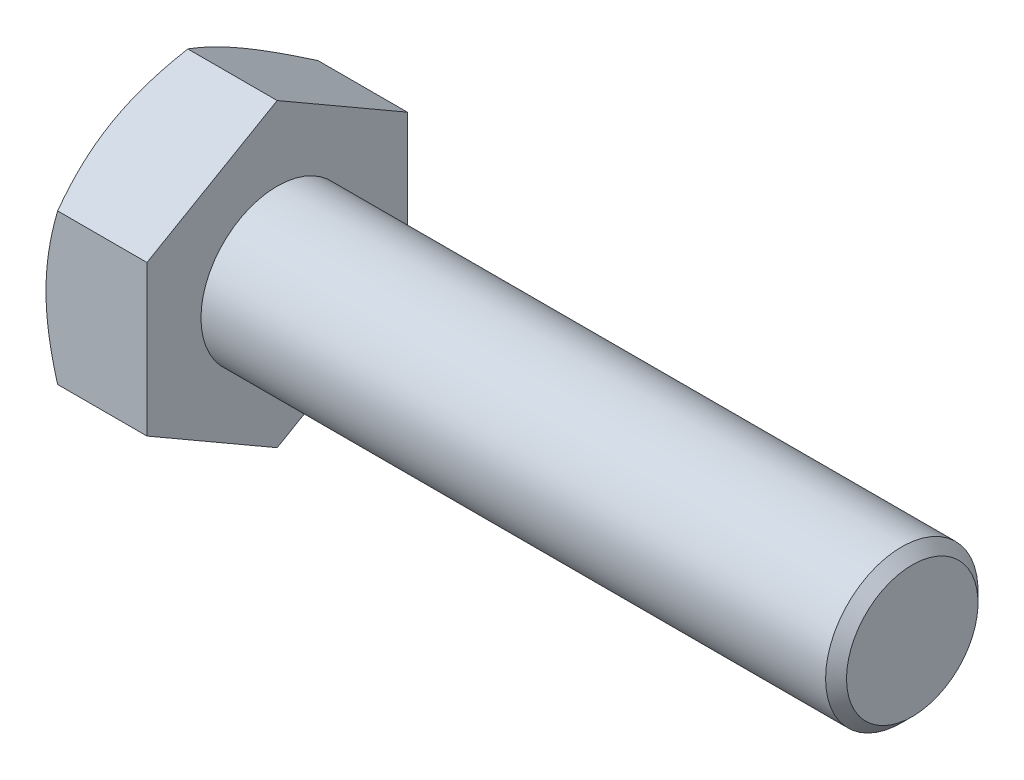
SolidWorks part; units mm, degrees
extrude "BaseHead" add sketch "Sketch1" along normal blind 15.9
sketch "Sketch1" plane through (0, 0, 0) normal (1, 0, 0) x (0, 0, -1)
  line L0 (20.5, 11.8357) -> (20.5, -11.8357)
  line L1 (-20.5, 11.8357) -> (-20.5, -11.8357)
  line L2 (20.5, -11.8357) -> (0, -23.6714)
  line L3 (0, -23.6714) -> (-20.5, -11.8357)
  line L4 (20.5, 11.8357) -> (0, 23.6714)
  line L5 (0, 23.6714) -> (-20.5, 11.8357)
  dimension "Width_flats" = 41
  dimension "D2" = 120
  dimension "D3" = 20.5
  dimension "D4" = 20.5
  dimension "D5" = 20.5
ref_plane "Plane1" through (0, 0, 0) normal (0, 0, 1) x (1, 0, 0)
ref_plane "Plane2" through (0, 0, 0) normal (0, 1, 0) x (1, 0, 0)
ref_plane "Plane3" through (0, 0, 0) normal (1, 0, 0) x (0, 0, -1)
sketch "BodySke" plane through (0, 0, 0) normal (0, 0, 1) x (1, 0, 0)
  line L0 (0, 11.8357) -> (0, -11.8357) construction
  line L1 (0, 0) -> (115.9, 0)
  line L2 (0, 0) -> (0, 12)
  line L3 (0, 12) -> (114.252, 12)
  line L4 (115.9, 0) -> (115.9, 10.352)
  line L5 (15.9, 23.6714) -> (15.9, 11.8357) construction
  line L6 (115.9, 10.352) -> (114.252, 12)
  line L7 (0, 0) -> (96.52, 0) construction
  line L8 (115.9, -10.352) -> (114.252, -12) construction
  line L9 (0, -12) -> (114.252, -12) construction
  line L10 (18.9, 15.24) -> (18.9, -1.27) construction
  line L11 (15.9, 15.24) -> (15.9, -1.27) construction
  line L12 (15.9, 11.8357) -> (15.9, -11.8357) construction
  dimension "Diameter" = 24
revolve "BaseBody" add sketch "BodySke"
cosmetic thread "ThreadCosmetic" [suppressed]
fillet "HeadFillet" [suppressed] radius 0.8
sketch "Sketch3" plane through (0, 0, 0) normal (0, 0, 1) x (1, 0, 0)
  line L0 (0, 20.5) -> (4.7177, 28.6714)
  line L1 (0, 23.6714) -> (0, 11.8357) construction
  line L2 (4.7177, 28.6714) -> (4.7177, 33.6714)
  line L3 (4.7177, 33.6714) -> (-10, 33.6714)
  line L4 (-10, 33.6714) -> (-10, 20.5)
  line L5 (-10, 20.5) -> (0, 20.5)
  line L6 (0, 0) -> (99.06, 0) construction
  line L7 (15.9, 23.6714) -> (0, 23.6714) construction
  dimension "D1" = 20.5
  dimension "D2" = 5
  dimension "D3" = 10
  dimension "D4" = 5
  dimension "Head_ch_ang" = 30
revolve "HeadChamfer" cut sketch "Sketch3" angle 360 about L6
sketch "ThdSchSke" plane through (0, 0, 0) normal (0, 0, 1) x (1, 0, 0)
  line L0 (18.9, -10.352) -> (17.7461, -12)
  line L1 (18.9, -10.352) -> (20.0539, -12)
  line L2 (20.0539, -12) -> (20.0539, -15)
  line L3 (-3.175, 0) -> (5.1513, 0) construction
  line L5 (20.0539, -15) -> (17.7461, -15)
  line L6 (17.7461, -15) -> (17.7461, -12)
  dimension "Thread_minor" = 20.704
  dimension "Diameter" = 24
  dimension "Start" = 18.9
revolve "ThreadSchematic" [suppressed] cut sketch "ThdSchSke" angle 360 about L3
pattern_linear "ThdSchPat" [suppressed]
equation "\"D3@Sketch1\" = \"Width_flats@Sketch1\" / 2"
equation "\"D4@Sketch1\" = \"D3@Sketch1\""
equation "\"D5@Sketch1\" = \"D4@Sketch1\""
equation "\"Thread_minor@ThreadCosmetic\" = \"Minor_dia@BodySke\""
equation "\"D1@Sketch3\" = \"Width_flats@Sketch1\" / 2"
equation "' \"D1@Sketch4\" = \"Width_flats@Sketch1\""
equation "\"Thread_length@ThreadCosmetic\" = ((sgn( (\"Length@BodySke\" - \"Advance@BodySke\" ) - \"Thread_nom@BodySke\" )-1)*( (\"Length@BodySke\" - \"Advance@BodySke\" ) - \"Thread_nom@BodySke\" ))/-2+ \"Thread_nom@BodySke\""
equation "\"Thread_minor@ThdSchSke\" = \"Minor_dia@BodySke\""
equation "\"Diameter@ThdSchSke\" = \"Diameter@BodySke\""
equation "\"Overcut@ThdSchSke\" = \"Diameter@BodySke\" * 1.25"
equation "\"Start@ThdSchSke\" = \"Head_ht@BaseHead\" + \"Length@BodySke\" - \"Thread_length@ThreadCosmetic\"  '---Non-countersunk---"
equation "\"Num_threads@ThdSchPat\" = int( \"Thread_length@ThreadCosmetic\" / \"Advance@BodySke\" + 0.999 )  + 1"
equation "\"Advance@ThdSchPat\" = \"Thread_length@ThreadCosmetic\" /  (\"Num_threads@ThdSchPat\" - 1) 'relax it"
equation "\"Num_threads@ThdSchPat\" = \"Num_threads@ThdSchPat\" - sgn( \"Num_threads@ThdSchPat\" - 1) '---chamfered tips only---"
